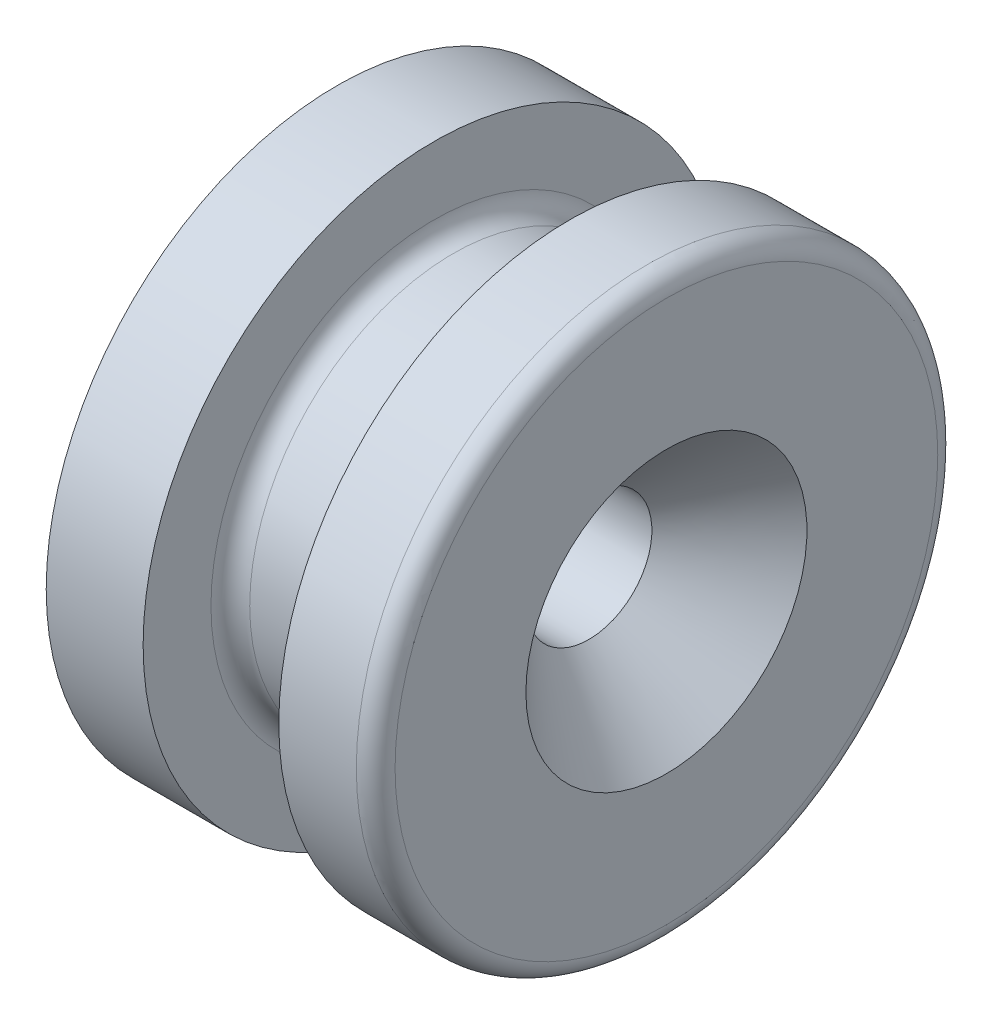
SolidWorks part; units mm, degrees
ref_plane "Ebene vorne" through (0, 0, 0) normal (0, 0, 1) x (1, 0, 0)
ref_plane "Ebene oben" through (0, 0, 0) normal (0, 1, 0) x (1, 0, 0)
ref_plane "Ebene rechts" through (0, 0, 0) normal (1, 0, 0) x (0, 0, -1)
sketch "Sketch1" plane through (0, 0, 0) normal (0, 0, 1) x (1, 0, 0)
  line L0 (-8.1219, 0) -> (30.7456, 0) construction
  line L1 (12, 15) -> (17, 15)
  line L3 (0, 3.25) -> (0, 15)
  line L4 (0, 15) -> (5, 15)
  line L5 (17, 3.25) -> (17, 15)
  line L6 (0, 3.25) -> (17, 3.25)
  line L7 (5, 15) -> (5, 10.5)
  line L8 (5, 10.5) -> (12, 10.5)
  line L9 (12, 15) -> (12, 10.5)
  point P11 (14.5, 15)
  dimension "D1" = 21
  dimension "D2" = 7
  dimension "D3" = 17
  dimension "D4" = 30
  dimension "D5" = 6.5
revolve "Revolve1" add sketch "Sketch1" angle 360 about L0
fillet "Fillet1" radius 1 1 edges at (17, 0, 15)
fillet "Fillet2" radius 1 2 edges at (12, 0, 10.5) (5, 0, 10.5)
chamfer "Chamfer1" distance 4 angle 45 1 edges at (17, 0, 3.25)
